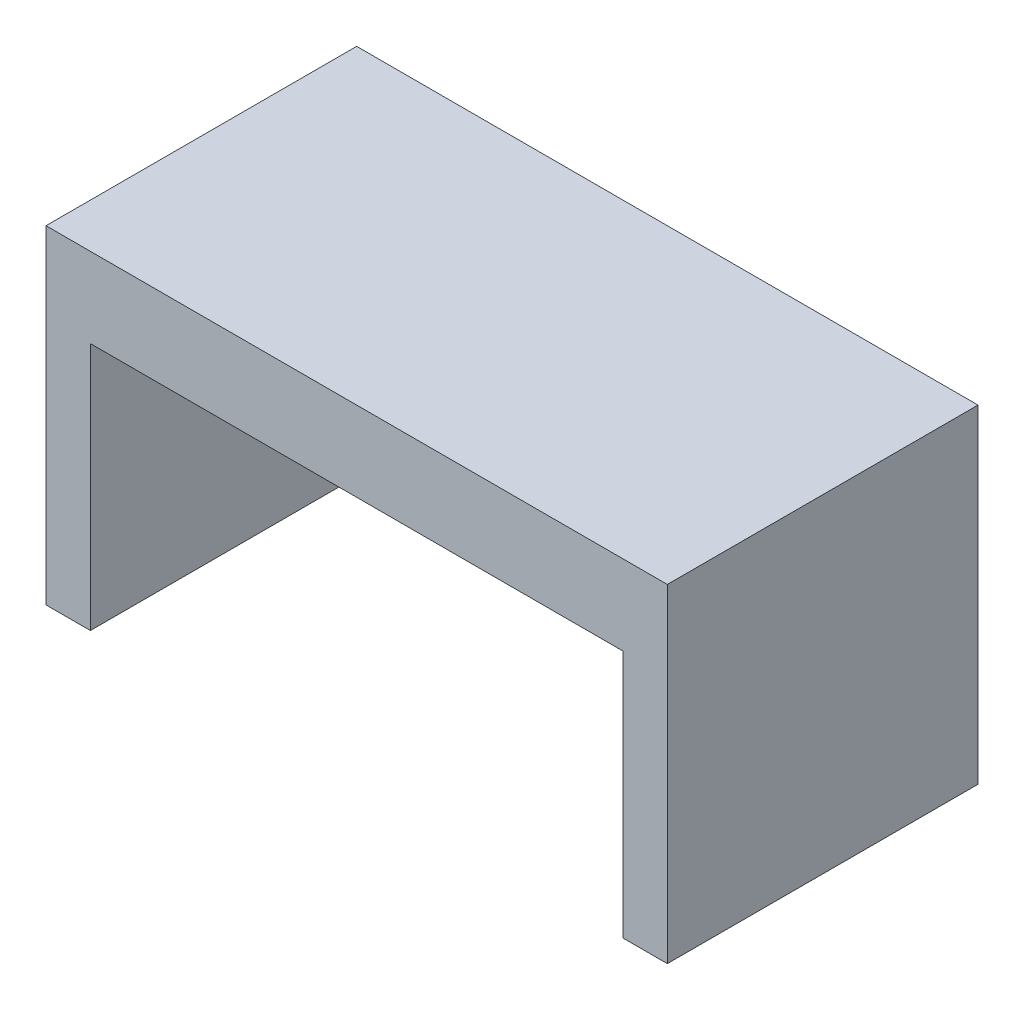
SolidWorks part; units mm, degrees
material "Pino"
ref_plane "Piano frontale" through (0, 0, 0) normal (0, 0, 1) x (1, 0, 0)
ref_plane "Piano superiore" through (0, 0, 0) normal (0, 1, 0) x (1, 0, 0)
ref_plane "Piano destro" through (0, 0, 0) normal (1, 0, 0) x (0, 0, -1)
sketch "Schizzo1" plane through (0, 0, 0) normal (0, 0, 1) x (1, 0, 0)
  line L0 (-100, 0) -> (0, 0)
  line L1 (0, 0) -> (0, 560)
  line L2 (0, 560) -> (1200, 560)
  line L3 (1200, 560) -> (1200, 0)
  line L4 (1200, 0) -> (1300, 0)
  line L5 (1300, 0) -> (1300, 740)
  line L6 (1300, 740) -> (-100, 740)
  line L7 (-100, 740) -> (-100, 0)
  point P4 (0, 0)
  point P9 (2144.2786, 1000)
  dimension "D1" = 740
  dimension "D2" = 100
  dimension "D3" = 180
  dimension "D4" = 1400
extrude "Estrusione-Estrusione1" add sketch "Schizzo1" along normal blind 700
